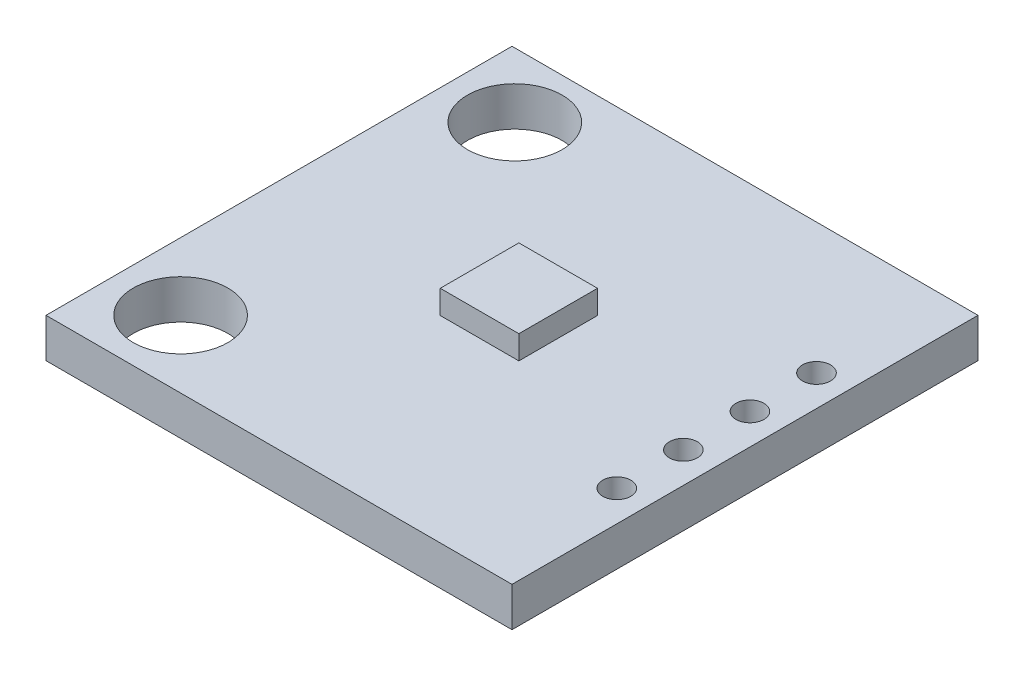
SolidWorks part; units mm, degrees
ref_plane "Front Plane" through (0, 0, 0) normal (0, 0, 1) x (1, 0, 0)
ref_plane "Top Plane" through (0, 0, 0) normal (0, 1, 0) x (1, 0, 0)
ref_plane "Right Plane" through (0, 0, 0) normal (1, 0, 0) x (0, 0, -1)
sketch "Sketch1" plane through (0, 0, 0) normal (0, 1, 0) x (1, 0, 0)
  line L1 (-29.8298, -21.481) -> (-12.0498, -21.481)
  line L2 (-29.8298, -21.481) -> (-29.8298, -39.261)
  line L3 (-29.8298, -39.261) -> (-12.0498, -39.261)
  line L4 (-12.0498, -21.481) -> (-12.0498, -39.261)
  dimension "D1" = 17.78
  dimension "D2" = 17.78
extrude "Boss-Extrude1" add sketch "Sketch1" along normal blind 1.5 contours L1 L4 L3 L2
sketch "Sketch2" plane through (0, 1.5, 0) normal (0, 1, 0) x (1, 0, 0)
  circle A0 centre (-27.2623, -23.9415) radius 1.8046
  circle A1 centre (-27.2623, -36.6935) radius 1.8046
  circle A2 centre (-13.2265, -26.4662) radius 0.5349
  circle A3 centre (-13.2265, -29.0062) radius 0.5349
  circle A4 centre (-13.2265, -31.5462) radius 0.5349
  circle A5 centre (-13.2265, -34.0862) radius 0.5349
  dimension "D1" = 4
extrude "Cut-Extrude1" cut sketch "Sketch2" against normal up to next
sketch "Sketch3" plane through (0, 1.5, 0) normal (0, 1, 0) x (1, 0, 0)
  line L1 (-22.3015, -28.747) -> (-19.3015, -28.747)
  line L2 (-22.3015, -28.747) -> (-22.3015, -31.747)
  line L3 (-22.3015, -31.747) -> (-19.3015, -31.747)
  line L4 (-19.3015, -28.747) -> (-19.3015, -31.747)
  dimension "D1" = 3
  dimension "D2" = 3
extrude "Boss-Extrude2" add sketch "Sketch3" along normal blind 0.9
